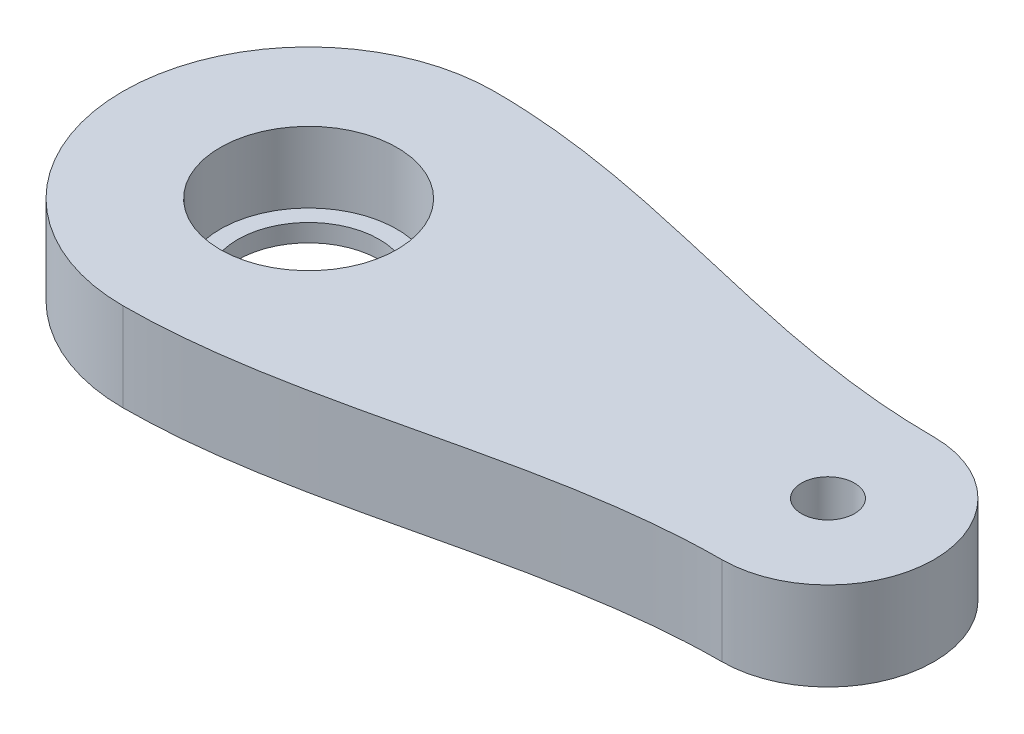
SolidWorks part; units mm, degrees
ref_plane "Front Plane" through (0, 0, 0) normal (0, 0, 1) x (1, 0, 0)
ref_plane "Top Plane" through (0, 0, 0) normal (0, 1, 0) x (1, 0, 0)
ref_plane "Right Plane" through (0, 0, 0) normal (1, 0, 0) x (0, 0, -1)
sketch "Sketch1" plane through (0, 0, 0) normal (0, 1, 0) x (1, 0, 0)
  line L0 (0, 0) -> (-29.37, 0) construction
  line L3 (-17.4889, 10.5) -> (-41.2511, 10.5) construction
  line L4 (8.1016, 6) -> (-8.1016, 6) construction
  line L5 (-17.4889, -10.5) -> (-41.2511, -10.5) construction
  line L6 (8.1016, -6) -> (-8.1016, -6) construction
  arc A0 (0, -6) -> (0, 6) centre (0, 0) ccw
  arc A2 (-29.37, 10.5) -> (-29.37, -10.5) centre (-29.37, 0) ccw
  spline S0 degree 3 poles (-29.37, 10.5) (-19.469, 10.5) (-10.1269, 6) (0, 6) knots 0 0 0 0 1 1 1 1
  spline S1 degree 3 poles (-29.37, -10.5) (-19.469, -10.5) (-10.1269, -6) (0, -6) knots 0 0 0 0 1 1 1 1
  point P3 (-14.68, 0)
  dimension "D3" = 21
  dimension "D1" = 6
  dimension "D2" = 29.37
extrude "Boss-Extrude1" add sketch "Sketch1" along normal blind 5
sketch "Sketch2" plane through (0, 5, 0) normal (0, 1, 0) x (1, 0, 0)
  circle A0 centre (0, 0) radius 1.5
  circle A1 centre (-29.37, 0) radius 5
  dimension "D1" = 3
  dimension "D2" = 10
extrude "Cut-Extrude1" cut sketch "Sketch2" against normal blind 4
sketch "Sketch3" plane through (0, 0, 0) normal (0, -1, 0) x (1, 0, 0)
  circle A0 centre (-29.37, 0) radius 4
  dimension "D1" = 8
extrude "Cut-Extrude2" cut sketch "Sketch3" against normal blind 10
sketch "Sketch4" plane through (0, 0, 0) normal (0, -1, 0) x (1, 0, 0)
  circle A0 centre (0, 0) radius 1.5
  dimension "D1" = 3
extrude "Cut-Extrude3" cut sketch "Sketch4" against normal blind 10
